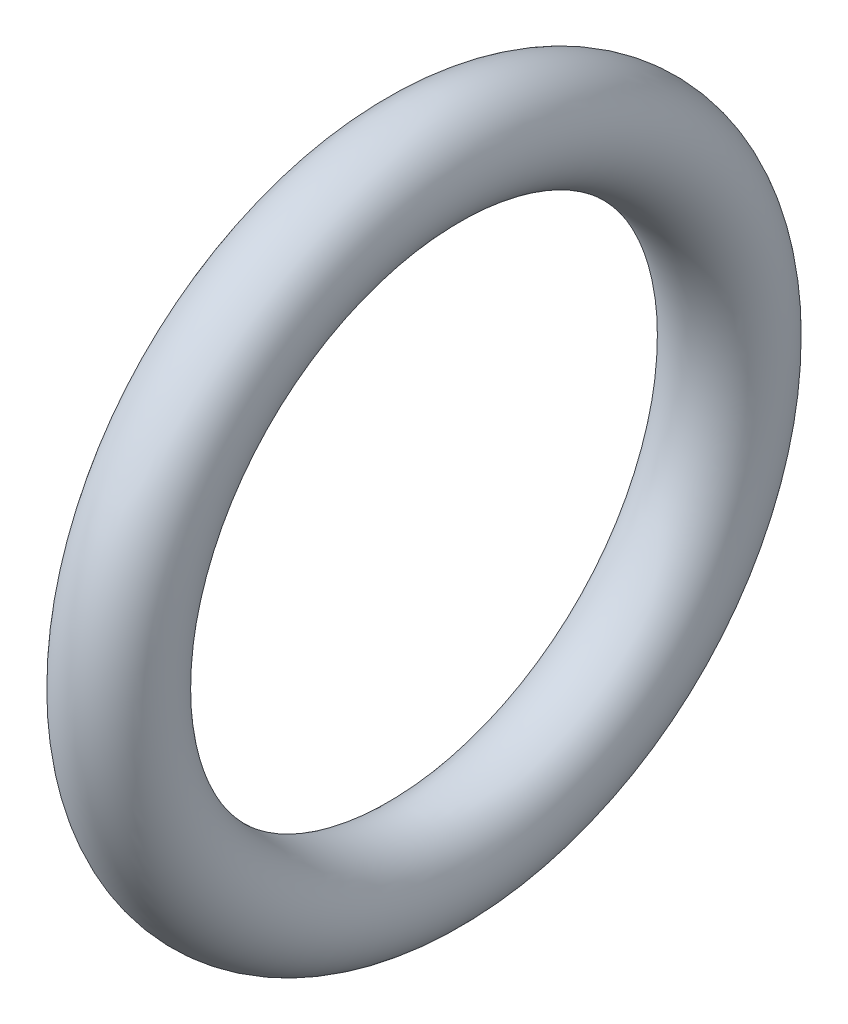
SolidWorks part; units mm, degrees
ref_plane "Спереди" through (0, 0, 0) normal (0, 0, 1) x (1, 0, 0)
ref_plane "Сверху" through (0, 0, 0) normal (0, 1, 0) x (1, 0, 0)
ref_plane "Справа" through (0, 0, 0) normal (1, 0, 0) x (0, 0, -1)
sketch "Эскиз1" plane through (0, 0, 0) normal (0, 0, 1) x (1, 0, 0)
  line L0 (0, 0) -> (11.9092, 0) construction
  circle A0 centre (0, 9) radius 1.5
  dimension "D1" = 3
  dimension "D2" = 7.5
revolve "Повернуть1" add sketch "Эскиз1" angle 360 about L0
